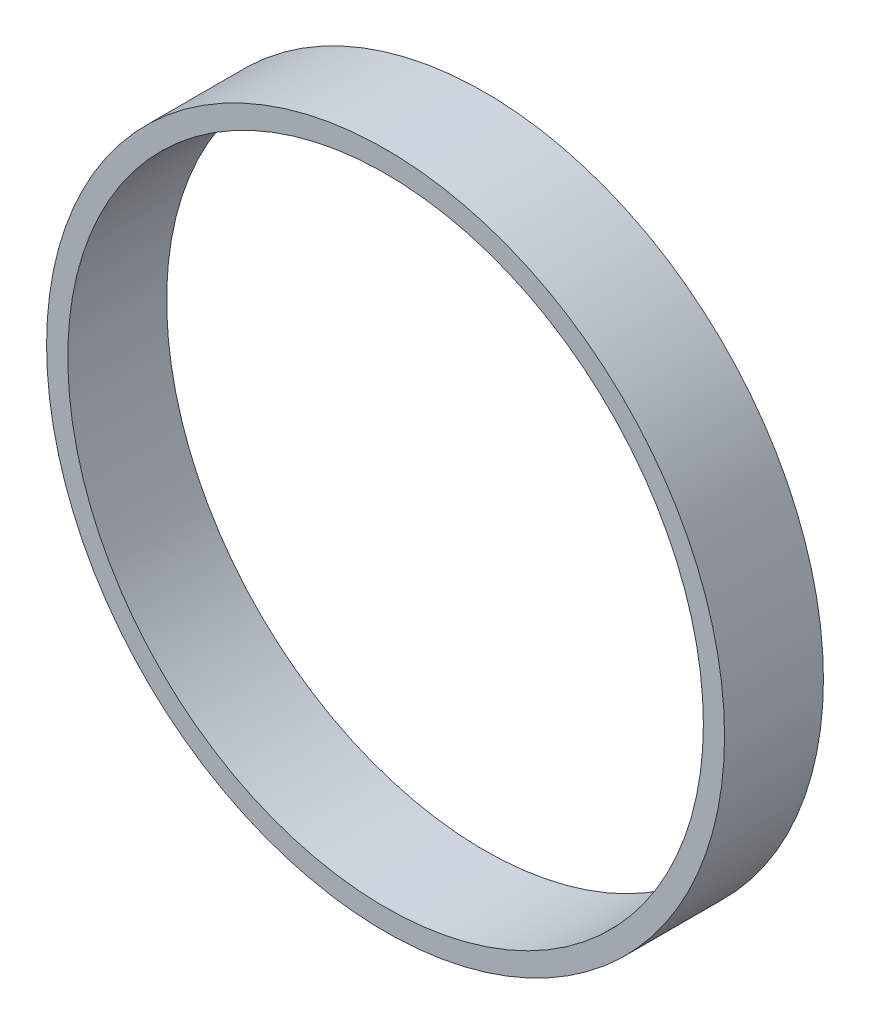
SolidWorks part; units mm, degrees
ref_plane "Front Plane" through (0, 0, 0) normal (0, 0, 1) x (1, 0, 0)
ref_plane "Top Plane" through (0, 0, 0) normal (0, 1, 0) x (1, 0, 0)
ref_plane "Right Plane" through (0, 0, 0) normal (1, 0, 0) x (0, 0, -1)
sketch "Sketch1" plane through (0, 0, 0) normal (0, 0, 1) x (1, 0, 0)
  circle A0 centre (0, 0) radius 24
  dimension "D1" = 48
extrude "Boss-Extrude1" add sketch "Sketch1" along normal blind 7 contours A0
sketch "Sketch2" plane through (0, 0, 7) normal (0, 0, 1) x (1, 0, 0)
  circle A0 centre (0, 0) radius 22.5
  dimension "D1" = 45
extrude "Cut-Extrude1" cut sketch "Sketch2" against normal blind 7
ref_plane "Plane1" through (0, 0, 3.5) normal (0, 0, 1) x (1, 0, 0)
